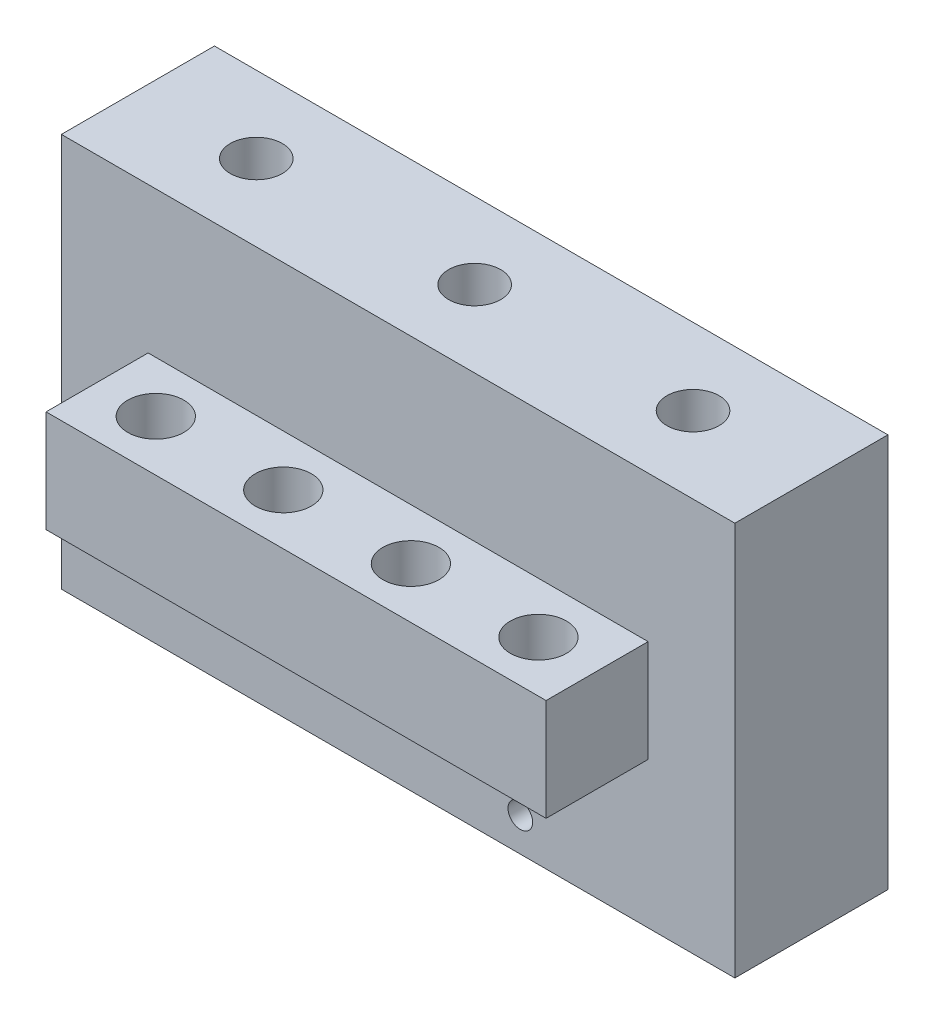
SolidWorks part; units mm, degrees
material "6061-T6 (SS)"
ref_plane "Front Plane" through (0, 0, 0) normal (0, 0, 1) x (1, 0, 0)
ref_plane "Top Plane" through (0, 0, 0) normal (0, 1, 0) x (1, 0, 0)
ref_plane "Right Plane" through (0, 0, 0) normal (1, 0, 0) x (0, 0, -1)
sketch "Sketch1" plane through (0, 0, 0) normal (0, 1, 0) x (1, 0, 0)
  line L0 (24.5, 0) -> (-24.5, 0)
  line L1 (-24.5, 0) -> (-24.5, 10)
  line L2 (-24.5, 10) -> (24.5, 10)
  line L3 (24.5, 0) -> (24.5, 10)
  point P4 (0, 0)
  dimension "D1" = 49
  dimension "D2" = 10
extrude "Boss-Extrude1" add sketch "Sketch1" along normal blind 10 contours L0 L1 L2 L3
sketch "Sketch2" plane through (0, 10, 0) normal (0, 1, 0) x (1, 0, 0)
  line L0 (-24.5, 5) -> (-18.75, 5) construction
  line L1 (-18.75, 5) -> (-18.75, 10) construction
  line L4 (24.5, 0) -> (24.5, 10)
  line L5 (24.5, 10) -> (-24.5, 10)
  line L6 (-24.5, 10) -> (-24.5, 0)
  line L7 (-24.5, 0) -> (24.5, 0)
  line L8 (24.5, 0) -> (24.5, 10) construction
  line L9 (24.5, 10) -> (-24.5, 10) construction
  line L10 (-24.5, 10) -> (-24.5, 0) construction
  line L11 (-24.5, 0) -> (24.5, 0) construction
  circle A0 centre (-18.75, 5) radius 2.75
  circle A1 centre (-6.25, 5) radius 2.75
  circle A2 centre (6.25, 5) radius 2.75
  circle A3 centre (18.75, 5) radius 2.75
  dimension "D3" = 5.5
  dimension "D2" = 5.75
  dimension "D1" = 0
  dimension "D4" = 4
extrude "Cut-Extrude1" cut sketch "Sketch2" against normal through all
sketch "Sketch3" plane through (0, 0, -10) normal (0, 0, -1) x (-1, 0, 0)
  line L0 (-24.5, 0) -> (-33, 0)
  line L1 (-24.5, 10) -> (-33, 10)
  line L2 (24.5, 10) -> (33, 10)
  line L3 (24.5, 0) -> (33, 0)
  line L4 (-24.5, 0) -> (24.5, 0)
  line L5 (24.5, 0) -> (24.5, 10)
  line L6 (24.5, 10) -> (-24.5, 10)
  line L7 (-24.5, 10) -> (-24.5, 0)
  line L8 (-24.5, 0) -> (24.5, 0)
  line L9 (24.5, 0) -> (24.5, 10)
  line L10 (24.5, 10) -> (-24.5, 10)
  line L11 (-24.5, 10) -> (-24.5, 0)
  line L12 (-33, 10) -> (-33, 0)
  line L13 (33, 10) -> (33, 0)
  line L14 (-24.5, 0) -> (-24.5, -7.5)
  line L15 (-24.5, 10) -> (-24.5, 17.5)
  line L16 (24.5, 10) -> (24.5, 17.5)
  line L17 (24.5, 0) -> (24.5, -7.5)
  line L18 (-24.5, -7.5) -> (24.5, -7.5)
  line L19 (24.5, 17.5) -> (-24.5, 17.5)
  line L20 (-33, 10) -> (-33, 17.5)
  line L21 (-24.5, 17.5) -> (-33, 17.5)
  line L22 (-24.5, -7.5) -> (-33, -7.5)
  line L23 (-33, 0) -> (-33, -7.5)
  line L24 (24.5, 17.5) -> (33, 17.5)
  line L25 (33, 17.5) -> (33, 10)
  line L26 (33, 0) -> (33, -7.5)
  line L27 (24.5, -7.5) -> (33, -7.5)
  dimension "D2" = 66
  dimension "D3" = 25
  dimension "D1" = 0
extrude "Boss-Extrude2" add sketch "Sketch3" along normal blind 15
sketch "Sketch11" plane through (0, 0, -25) normal (0, 0, -1) x (-1, 0, 0)
  line L4 (-33, -7.5) -> (33, -7.5)
  line L5 (33, -7.5) -> (33, 17.5)
  line L6 (33, 17.5) -> (-33, 17.5)
  line L7 (-33, 17.5) -> (-33, -7.5)
  line L8 (-33, -7.5) -> (33, -7.5)
  line L9 (33, -7.5) -> (33, 17.5)
  line L10 (33, 17.5) -> (-33, 17.5)
  line L11 (-33, 17.5) -> (-33, -7.5)
  line L16 (-7.8, -14.3) -> (7.8, -14.3)
  line L17 (-7.8, 24.3) -> (7.8, 24.3)
  line L18 (-7.8, 24.3) -> (-7.8, 27.5) construction
  line L19 (7.8, 24.3) -> (7.8, 27.5) construction
  line L20 (-7.8, -17.5) -> (7.8, -17.5) construction
  line L21 (-7.8, -17.5) -> (-7.8, -14.3) construction
  line L22 (7.8, -17.5) -> (7.8, -14.3) construction
  line L23 (-7.8, 27.5) -> (7.8, 27.5) construction
  line L24 (7.8, 24.3) -> (33, 24.3)
  line L25 (33, 17.5) -> (33, 24.3)
  line L26 (-7.8, 24.3) -> (-33, 24.3)
  line L27 (-33, 17.5) -> (-33, 24.3)
  line L28 (-7.8, -14.3) -> (-33, -14.3)
  line L29 (-33, -7.5) -> (-33, -14.3)
  line L30 (7.8, -14.3) -> (33, -14.3)
  line L31 (33, -7.5) -> (33, -14.3)
  line L32 (7.8, -17.5) -> (33, -17.5) construction
  line L33 (33, -14.3) -> (33, -17.5) construction
  line L34 (-7.8, -17.5) -> (-33, -17.5) construction
  line L35 (-33, -14.3) -> (-33, -17.5) construction
  line L36 (-7.8, 27.5) -> (-33, 27.5) construction
  line L37 (-33, 24.3) -> (-33, 27.5) construction
  line L38 (7.8, 27.5) -> (33, 27.5) construction
  line L39 (33, 24.3) -> (33, 27.5) construction
  line L40 (-9.8, 24.3) -> (-9.8, 27.5) construction
  line L41 (9.8, 24.3) -> (9.8, 27.5) construction
  line L42 (-9.8, -14.3) -> (-9.8, -17.5) construction
  line L43 (9.8, -14.3) -> (9.8, -17.5) construction
  line L44 (7.8, 24.3) -> (-7.8, 24.3) construction
  line L45 (-7.8, -14.3) -> (7.8, -14.3) construction
  line L46 (7.8, 24.3) -> (-7.8, 24.3)
  line L47 (-7.8, -14.3) -> (7.8, -14.3)
  line L48 (-6.8, -17.5) -> (6.8, -17.5) construction
  line L49 (6.8, 27.5) -> (-6.8, 27.5) construction
  line L50 (-6.8, -17.5) -> (6.8, -17.5) construction
  line L51 (6.8, 27.5) -> (-6.8, 27.5) construction
  dimension "D2" = 2
  dimension "D3" = 2
  dimension "D4" = 2
  dimension "D5" = 2
  dimension "D1" = 0
extrude "Boss-Extrude3" add sketch "Sketch11" against normal up to surface (15 mm away) up to face at (0, 5, -10)
hole_wizard "1/4-20 Tapped Hole1" positions "Sketch12" profile "Sketch13" tap size "1/4-20" standard "ANSI Inch" end condition through all
sketch "Sketch12" plane through (0, -14.3, 0) normal (0, -1, 0) x (-1, 0, 0)
  line L10 (-33, 10) -> (33, 10)
  line L12 (33, 25) -> (-33, 25)
  line L14 (-33, 10) -> (33, 10)
  line L16 (33, 25) -> (-33, 25)
  line L17 (-9.8, 17.5) -> (0, 17.5) construction
  line L18 (0, 10) -> (0, 17.5) construction
  line L55 (-33, 25) -> (-33, 10)
  line L56 (-33, 25) -> (-33, 10)
  line L57 (33, 10) -> (33, 25)
  line L58 (33, 10) -> (33, 25)
  point P0 (0, 17.5)
  dimension "D1" = 0
sketch "Sketch13" plane through (0, -14.3, -17.5) normal (1, 0, 0) x (0, 0, -1)
  line L0 (0, 0) -> (0, 38.6)
  line L1 (0, 38.6) -> (2.5527, 38.6)
  line L2 (2.5527, 38.6) -> (2.5527, 0)
  line L5 (2.5527, 0) -> (0, 0)
  line L11 (0, -6.35) -> (0, 107.95) construction
  dimension "Thread Major Dia." = 5.1054
  dimension "Thru Tap Drill Depth" = 38.6
hole_wizard "1/4-20 Tapped Hole2" positions "Sketch15" profile "Sketch16" tap size "1/4-20" standard "ANSI Inch" end condition through all
sketch "Sketch15" plane through (0, -14.3, 0) normal (0, -1, 0) x (-1, 0, 0)
  line L18 (9.8, 10) -> (33, 10)
  line L20 (33, 25) -> (9.8, 25)
  line L35 (-33, 10) -> (-9.8, 10)
  line L37 (-9.8, 25) -> (-33, 25)
  line L38 (21.4, 10) -> (21.4, 25) construction
  line L39 (-21.4, 10) -> (-21.4, 25) construction
  line L41 (33, 10) -> (33, 25) construction
  line L42 (33, 10) -> (33, 25)
  line L44 (-33, 10) -> (33, 10) construction
  line L45 (-33, 10) -> (33, 10) construction
  line L47 (-33, 10) -> (-33, 25) construction
  line L48 (-33, 10) -> (-33, 25)
  line L49 (33, 25) -> (-33, 25) construction
  point P0 (21.4, 17.5)
  point P2 (-21.4, 17.5)
  dimension "D1" = 23.2
sketch "Sketch16" plane through (-21.4, -14.3, -17.5) normal (1, 0, 0) x (0, 0, -1)
  line L0 (0, 0) -> (0, 38.6)
  line L1 (0, 38.6) -> (2.5527, 38.6)
  line L2 (2.5527, 38.6) -> (2.5527, 0)
  line L5 (2.5527, 0) -> (0, 0)
  line L11 (0, -6.35) -> (0, 107.95) construction
  dimension "Thread Major Dia." = 5.1054
  dimension "Thru Tap Drill Depth" = 38.6
sketch "Sketch17" plane through (0, 0, -25) normal (0, 0, -1) x (-1, 0, 0)
  ellipse E0 centre (-11.9761, -11) end of major axis (-10.7696, -11) minor radius 1.2059 construction
  ellipse E1 centre (-11.9761, -11) end of major axis (-10.7696, -11) minor radius 1.2059
extrude "Torsional Spring Mount Hole" cut sketch "Sketch17" against normal through all
